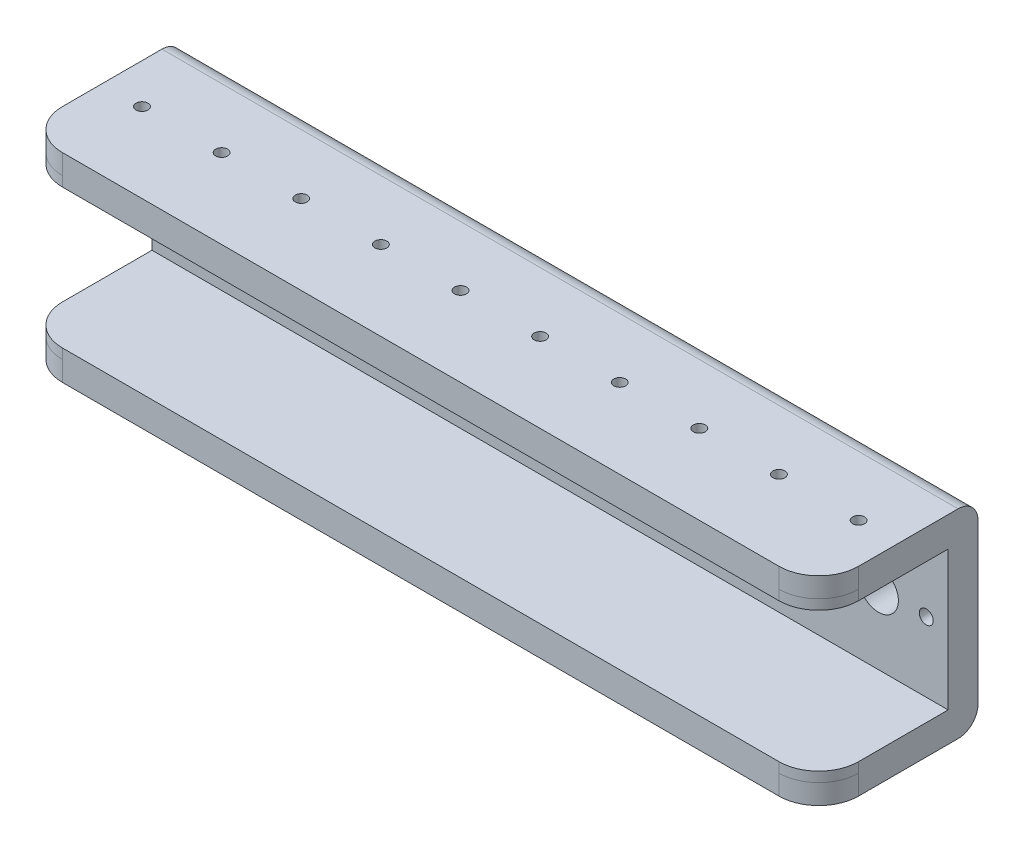
SolidWorks part; units mm, degrees
ref_plane "Front Plane" through (0, 0, 0) normal (0, 0, 1) x (1, 0, 0)
ref_plane "Top Plane" through (0, 0, 0) normal (0, 1, 0) x (1, 0, 0)
ref_plane "Right Plane" through (0, 0, 0) normal (1, 0, 0) x (0, 0, -1)
sketch "Sketch1" plane through (0, 0, 0) normal (0, 1, 0) x (1, 0, 0)
  line L1 (-64.0787, 63.2893) -> (335.9213, 63.2893)
  line L2 (-64.0787, 63.2893) -> (-64.0787, -16.7107)
  line L3 (-64.0787, -16.7107) -> (335.9213, -16.7107)
  line L4 (335.9213, 63.2893) -> (335.9213, -16.7107)
  dimension "D1" = 400
  dimension "D2" = 80
extrude "Boss-Extrude1" add sketch "Sketch1" along normal blind 10
sketch "Sketch2" plane through (0, 10, 0) normal (0, 1, 0) x (1, 0, 0)
  line L0 (335.9213, -16.7107) -> (335.9213, 63.2893) construction
  line L1 (-64.0787, 63.2893) -> (335.9213, 63.2893)
  line L2 (-64.0787, 63.2893) -> (-64.0787, 53.2893)
  line L3 (-64.0787, 53.2893) -> (335.9213, 53.2893)
  line L4 (335.9213, 63.2893) -> (335.9213, 53.2893)
  dimension "D1" = 10
extrude "Boss-Extrude2" add sketch "Sketch2" along normal blind 80
sketch "Sketch3" plane through (0, 90, 0) normal (0, 1, 0) x (1, 0, 0)
  line L1 (-64.0787, 53.2893) -> (335.9213, 53.2893)
  line L2 (-64.0787, 53.2893) -> (-64.0787, 63.2893)
  line L3 (-64.0787, 63.2893) -> (335.9213, 63.2893)
  line L4 (335.9213, 53.2893) -> (335.9213, 63.2893)
extrude "Boss-Extrude3" add sketch "Sketch3" along normal blind 10
sketch "Sketch4" plane through (0, 0, -53.2893) normal (0, 0, 1) x (1, 0, 0)
  line L0 (335.9213, 100) -> (335.9213, 10) construction
  line L1 (-64.0787, 100) -> (335.9213, 100)
  line L2 (-64.0787, 100) -> (-64.0787, 90)
  line L3 (-64.0787, 90) -> (335.9213, 90)
  line L4 (335.9213, 100) -> (335.9213, 90)
  dimension "D1" = 10
extrude "Boss-Extrude4" add sketch "Sketch4" along normal blind 70
fillet "Fillet1" radius 20 4 edges at (-64.0787, 95, 16.7107) (335.9213, 95, 16.7107) (-64.0787, 5, 16.7107) (335.9213, 5, 16.7107)
fillet "Fillet2" radius 10 2 edges at (135.9213, 0, -63.2893) (135.9213, 100, -63.2893)
sketch "Sketch5" plane through (0, 0, -63.2893) normal (0, 0, -1) x (-1, 0, 0)
  line L0 (-335.9213, 50) -> (-310.9213, 50)
  line L1 (64.0787, 50) -> (39.0787, 50)
  line L3 (64.0787, 10) -> (64.0787, 90)
  line L4 (-335.9213, 90) -> (-335.9213, 10) construction
  circle A0 centre (-135.9213, 50) radius 8.5
  circle A1 centre (-310.9213, 50) radius 10
  circle A2 centre (39.0787, 50) radius 10
  circle A3 centre (-109.4213, 50) radius 3.5
  circle A4 centre (-162.4213, 50) radius 3.5
  dimension "D6" = 20
  dimension "D7" = 20
  dimension "D1" = 80
  dimension "D2" = 400
  dimension "D4" = 25
  dimension "D5" = 25
sketch "Sketch7" plane through (0, 0, -63.2893) normal (0, 0, -1) x (-1, 0, 0)
  line L1 (64.0787, 50) -> (39.0787, 50) construction
  circle A0 centre (-135.9213, 50) radius 8.5
  circle A1 centre (-109.4213, 50) radius 3.5
  circle A2 centre (-162.4213, 50) radius 3.5
  circle A3 centre (-310.9213, 50) radius 10 construction
  circle A4 centre (-324.9213, 50) radius 3.5
  circle A5 centre (-300.9213, 50) radius 10
  circle A6 centre (-276.9213, 50) radius 3.5
  circle A7 centre (39.0787, 50) radius 10 construction
  circle A8 centre (53.0787, 50) radius 3.5
  circle A9 centre (29.0787, 50) radius 10
  circle A10 centre (5.0787, 50) radius 3.5
  dimension "D1" = 7
  dimension "D2" = 7
  dimension "D3" = 7
  dimension "D4" = 20
  dimension "D5" = 7
extrude "Cut-Extrude1" cut sketch "Sketch7" against normal blind 10
sketch "Sketch8" plane through (0, 100, 0) normal (0, 1, 0) x (1, 0, 0)
  circle A0 centre (-44.0787, 23.2893) radius 3
  circle A1 centre (-4.0787, 23.2893) radius 3
  circle A2 centre (35.9213, 23.2893) radius 3
  circle A3 centre (75.9213, 23.2893) radius 3
  circle A4 centre (115.9213, 23.2893) radius 3
  circle A5 centre (155.9213, 23.2893) radius 3
  circle A6 centre (195.9213, 23.2893) radius 3
  circle A7 centre (235.9213, 23.2893) radius 3
  circle A8 centre (275.9213, 23.2893) radius 3
  circle A9 centre (315.9213, 23.2893) radius 3
extrude "Cut-Extrude2" cut sketch "Sketch8" against normal up to next
sketch "Sketch9" plane through (0, 0, -53.2893) normal (0, 0, 1) x (1, 0, 0)
  line L1 (-64.0787, 90) -> (335.9213, 90)
  line L2 (-64.0787, 90) -> (-64.0787, 10)
  line L3 (-64.0787, 10) -> (335.9213, 10)
  line L4 (335.9213, 90) -> (335.9213, 10)
  circle A0 centre (-29.0787, 50) radius 10
  circle A1 centre (-5.0787, 50) radius 3.5
  circle A2 centre (-53.0787, 50) radius 3.5
  circle A3 centre (135.9213, 50) radius 8.5
  circle A4 centre (109.4213, 50) radius 3.5
  circle A5 centre (162.4213, 50) radius 3.5
  circle A6 centre (300.9213, 50) radius 10
  circle A7 centre (324.9213, 50) radius 3.5
  circle A8 centre (276.9213, 50) radius 3.5
extrude "Boss-Extrude5" add sketch "Sketch9" along normal blind 5
sketch "Sketch10" plane through (0, 90, 0) normal (0, -1, 0) x (1, 0, 0)
  line L1 (-64.0787, -48.2893) -> (335.9213, -48.2893)
  line L2 (-64.0787, -48.2893) -> (-64.0787, 16.7107)
  line L3 (-64.0787, 16.7107) -> (335.9213, 16.7107)
  line L4 (335.9213, -48.2893) -> (335.9213, 16.7107)
  circle A0 centre (-44.0787, -23.2893) radius 3
  circle A1 centre (-4.0787, -23.2893) radius 3
  circle A2 centre (35.9213, -23.2893) radius 3
  circle A3 centre (75.9213, -23.2893) radius 3
  circle A4 centre (115.9213, -23.2893) radius 3
  circle A5 centre (155.9213, -23.2893) radius 3
  circle A6 centre (195.9213, -23.2893) radius 3
  circle A7 centre (235.9213, -23.2893) radius 3
  circle A8 centre (275.9213, -23.2893) radius 3
  circle A9 centre (315.9213, -23.2893) radius 3
extrude "Boss-Extrude6" add sketch "Sketch10" along normal blind 5
sketch "Sketch11" plane through (0, 10, 0) normal (0, 1, 0) x (1, 0, 0)
  line L1 (-64.0787, 48.2893) -> (335.9213, 48.2893)
  line L2 (-64.0787, 48.2893) -> (-64.0787, -16.7107)
  line L3 (-64.0787, -16.7107) -> (335.9213, -16.7107)
  line L4 (335.9213, 48.2893) -> (335.9213, -16.7107)
extrude "Boss-Extrude7" add sketch "Sketch11" along normal blind 5
fillet "Fillet3" radius 20 4 edges at (335.9213, 12.5, 16.7107) (335.9213, 87.5, 16.7107) (-64.0787, 12.5, 16.7107) (-64.0787, 87.5, 16.7107)
